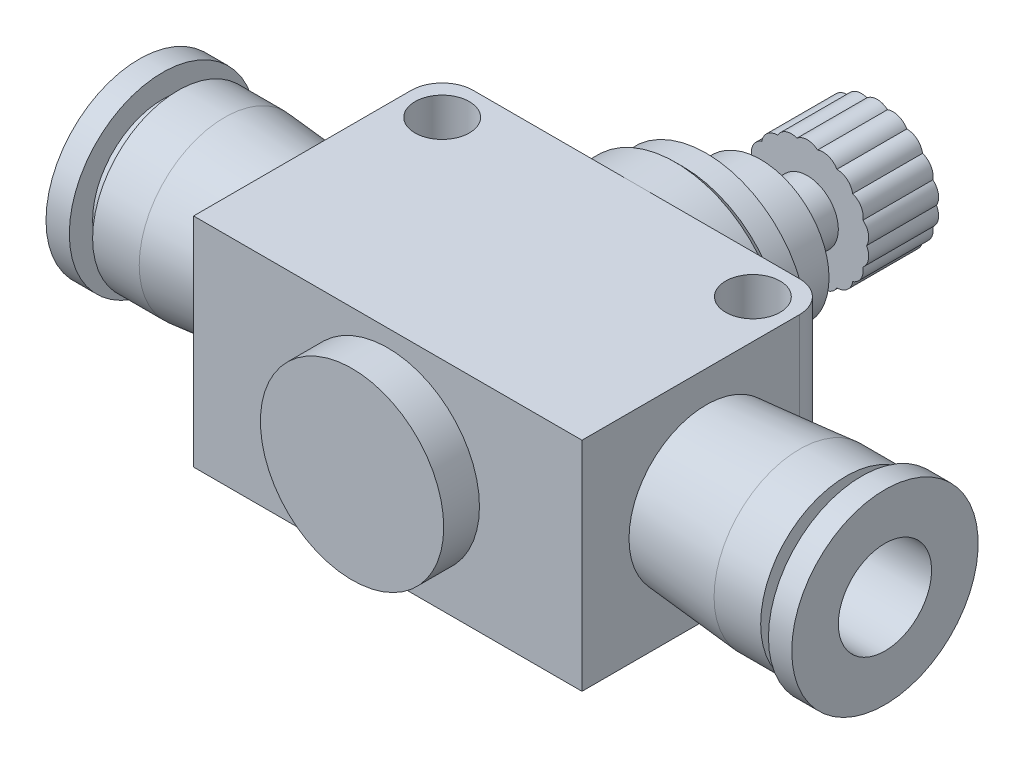
SolidWorks part; units mm, degrees
ref_plane "前视基准面" through (0, 0, 0) normal (0, 0, 1) x (1, 0, 0)
ref_plane "上视基准面" through (0, 0, 0) normal (0, 1, 0) x (1, 0, 0)
ref_plane "右视基准面" through (0, 0, 0) normal (1, 0, 0) x (0, 0, -1)
sketch "草图1" plane through (0, 0, 0) normal (0, 1, 0) x (1, 0, 0)
  line L1 (-12.5, -8) -> (12.5, -8)
  line L2 (-12.5, -8) -> (-12.5, 8)
  line L3 (-12.5, 8) -> (12.5, 8)
  line L4 (12.5, -8) -> (12.5, 8)
  line L5 (-12.5, -8) -> (12.5, 8) construction
  line L6 (-12.5, 8) -> (12.5, -8) construction
  point P0 (0, 0)
  dimension "D1" = 25
  dimension "D2" = 16
extrude "凸台-拉伸1" add sketch "草图1" along normal mid plane 14
sketch "草图2" plane through (0, 0, 0) normal (0, 1, 0) x (1, 0, 0)
  line L0 (-12.5, 4.9751) -> (-18.5, 5.5)
  line L1 (-12.5, 8) -> (-12.5, -8) construction
  line L2 (-18.5, 5.5) -> (-21.5, 5.5)
  line L3 (-21.5, 5.5) -> (-21.5, 4.5)
  line L4 (-21.5, 4.5) -> (-22.5, 4.5)
  line L5 (-22.5, 4.5) -> (-22.5, 6)
  line L6 (-22.5, 6) -> (-24, 6)
  line L7 (-24, 6) -> (-24, 3)
  line L8 (-12.5, 4.9751) -> (-12.5, 2)
  line L9 (-27.0606, 0) -> (27.0606, 0) construction
  line L10 (-24, 3) -> (-19.5, 3)
  line L11 (-19.5, 3) -> (-19.5, 2)
  line L12 (-19.5, 2) -> (-12.5, 2)
  line L13 (0, 0) -> (0, 17.9963) construction
  line L14 (19.5, 2) -> (12.5, 2)
  line L15 (19.5, 3) -> (19.5, 2)
  line L16 (24, 3) -> (19.5, 3)
  line L17 (12.5, 4.9751) -> (12.5, 2)
  line L18 (24, 6) -> (24, 3)
  line L19 (22.5, 6) -> (24, 6)
  line L20 (22.5, 4.5) -> (22.5, 6)
  line L21 (21.5, 4.5) -> (22.5, 4.5)
  line L22 (21.5, 5.5) -> (21.5, 4.5)
  line L23 (18.5, 5.5) -> (21.5, 5.5)
  line L24 (12.5, 4.9751) -> (18.5, 5.5)
  point P15 (0, 0)
  dimension "D1" = 12
  dimension "D2" = 1.5
  dimension "D3" = 1
  dimension "D4" = 9
  dimension "D5" = 11
  dimension "D6" = 175
  dimension "D7" = 3
  dimension "D8" = 6
  dimension "D9" = 6
  dimension "D10" = 4
  dimension "D11" = 4.5
  dimension "D12" = 11.5
revolve "旋转1" add sketch "草图2" angle 360 about L9
sketch "草图3" plane through (0, 0, 0) normal (0, 1, 0) x (1, 0, 0)
  line L0 (7, 8) -> (7, 10.5)
  line L1 (12.5, 8) -> (-12.5, 8) construction
  line L2 (4, 13.5) -> (4.4, 13.5)
  line L3 (6.5, 11) -> (7, 10.5)
  line L4 (6.5, 11) -> (6.5, 12.5)
  line L5 (6.5, 12.5) -> (4, 12.5)
  line L6 (4, 12.5) -> (4, 13.5)
  line L7 (5.9, -8) -> (5.9, -10.3)
  line L8 (4.4, 13.5) -> (4.4, 16)
  line L9 (4.4, 16) -> (2, 16)
  line L10 (2, 16) -> (2, 19)
  line L11 (2, 19) -> (4, 19)
  line L12 (4, 19) -> (4, 23.5)
  line L13 (4, 23.5) -> (0, 23.5)
  line L14 (0, 23.5) -> (0, 8)
  line L15 (0, 8) -> (7, 8)
  line L16 (0, -30.0217) -> (0, 30.0217) construction
  line L17 (-12.5, -8) -> (12.5, -8) construction
  line L18 (5.9, -10.3) -> (0, -10.3)
  line L19 (0, -10.3) -> (0, -8)
  line L20 (0, -8) -> (5.9, -8)
  point P21 (0, 0)
  dimension "D2" = 14
  dimension "D3" = 4.5
  dimension "D4" = 1.5
  dimension "D5" = 8
  dimension "D6" = 13
  dimension "D7" = 135
  dimension "D8" = 3
  dimension "D9" = 1
  dimension "D10" = 2.5
  dimension "D11" = 15.5
  dimension "D12" = 11.8
  dimension "D13" = 8.8
  dimension "D14" = 8
  dimension "D15" = 4
  dimension "D16" = 3
  dimension "D17" = 2.3
revolve "旋转2" add sketch "草图3" angle 360 about L16
fillet "圆角1" radius 2 2 edges at (12.5, 0, -8) (-12.5, 0, -8)
sketch "草图4" plane through (0, 7, 0) normal (0, 1, 0) x (1, 0, 0)
  line L0 (0, 12.907) -> (0, -12.907) construction
  circle A0 centre (-10, 5.5) radius 1.75
  circle A1 centre (10, 5.5) radius 1.75
  point P8 (0, 0)
  dimension "D1" = 3.5
  dimension "D2" = 20
  dimension "D3" = 5.5
extrude "切除-拉伸1" cut sketch "草图4" against normal through all
sketch "草图5" plane through (0, 0, -23.5) normal (0, 0, -1) x (-1, 0, 0)
  line L0 (0, 0) -> (0, 5.2913) construction
  line L1 (0, 0) -> (1.8075, 4.9662) construction
  circle A0 centre (0, 0) radius 3.814 construction
  arc A1 (0, 4) -> (0.6623, 3.7561) centre (0, 2.979) cw
  circle A2 centre (0, 0) radius 4 construction
  arc A3 (0.6623, 3.7561) -> (1.3681, 3.7588) centre (1.0189, 2.7993) cw
  arc A4 (0, 4) -> (1.3681, 3.7588) centre (0, 0) cw
  dimension "D1" = 20
extrude "切除-拉伸2" cut sketch "草图5" against normal up to surface (4.5 mm away) contours A1 A3 A4 up to face at (4, 0, -19)
fillet "圆角2" [suppressed] radius 0.5
pattern_circular "阵列(圆周)1" count 18 over 360 about axis through (0, 0, 0) along (0, 0, 1) of "切除-拉伸2", "圆角2"
